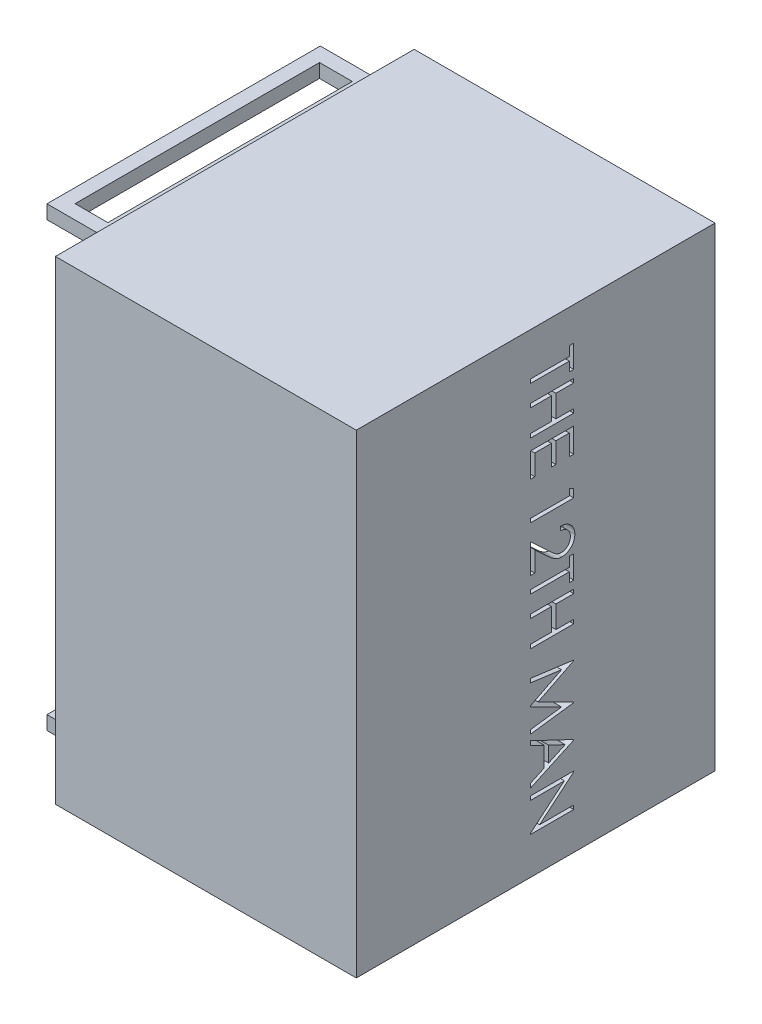
SolidWorks part; units mm, degrees
ref_plane "Front Plane" through (0, 0, 0) normal (0, 0, 1) x (1, 0, 0)
ref_plane "Top Plane" through (0, 0, 0) normal (0, 1, 0) x (1, 0, 0)
ref_plane "Right Plane" through (0, 0, 0) normal (1, 0, 0) x (0, 0, -1)
sketch "Sketch1" plane through (0, 0, 0) normal (0, 0, 1) x (1, 0, 0)
  line L0 (0, 0) -> (66.04, 0)
  line L1 (66.04, 0) -> (66.04, 104.14)
  line L2 (66.04, 104.14) -> (0, 104.14)
  line L3 (0, 104.14) -> (0, 0)
  dimension "D1" = 66.04
  dimension "D2" = 104.14
extrude "Boss-Extrude1" add sketch "Sketch1" along normal blind 78.74
shell "Shell3" thickness 2.54
sketch "Sketch6" plane through (66.04, 0, 0) normal (1, 0, 0) x (0, 0, -1)
  line L0 (-40.5448, 104.14) -> (-40.5448, 0) construction
  line L1 (-78.74, 104.14) -> (0, 104.14) construction
  line L2 (-78.74, 0) -> (0, 0) construction
  text T0 "THE 12TH MAN" font "Century Gothic" height in points 36
extrude "Cut-Extrude7" cut sketch "Sketch6" against normal blind 40.64
sketch "Sketch7" plane through (0, 0, 0) normal (-1, 0, 0) x (0, 0, 1)
  line L0 (39.37, 104.14) -> (39.37, 0) construction
  line L1 (78.74, 104.14) -> (0, 104.14) construction
  line L2 (78.74, 0) -> (0, 0) construction
  text T0 "THE 12TH MAN" font "Century Gothic" height in points 36
extrude "Cut-Extrude9" cut sketch "Sketch7" against normal blind 40.64
sketch "Sketch8" plane through (0, 0, 0) normal (-1, 0, 0) x (0, 0, 1)
  line L1 (7.9065, 5.272) -> (67.8951, 5.272)
  line L2 (7.9065, 5.272) -> (7.9065, 2.2422)
  line L3 (7.9065, 2.2422) -> (67.8951, 2.2422)
  line L4 (67.8951, 5.272) -> (67.8951, 2.2422)
  line L5 (7.9065, 102.3747) -> (67.8951, 102.3747)
  line L6 (7.9065, 102.3747) -> (7.9065, 99.345)
  line L7 (7.9065, 99.345) -> (67.8951, 99.345)
  line L8 (67.8951, 102.3747) -> (67.8951, 99.345)
extrude "Boss-Extrude3" add sketch "Sketch8" along normal blind 12.7
sketch "Sketch9" plane through (0, 102.3747, 0) normal (0, 1, 0) x (1, 0, 0)
  line L1 (-9.6397, -11.1332) -> (-2.437, -11.1332)
  line L2 (-9.6397, -11.1332) -> (-9.6397, -64.7883)
  line L3 (-9.6397, -64.7883) -> (-2.437, -64.7883)
  line L4 (-2.437, -11.1332) -> (-2.437, -64.7883)
extrude "Cut-Extrude10" cut sketch "Sketch9" against normal blind 111.76
